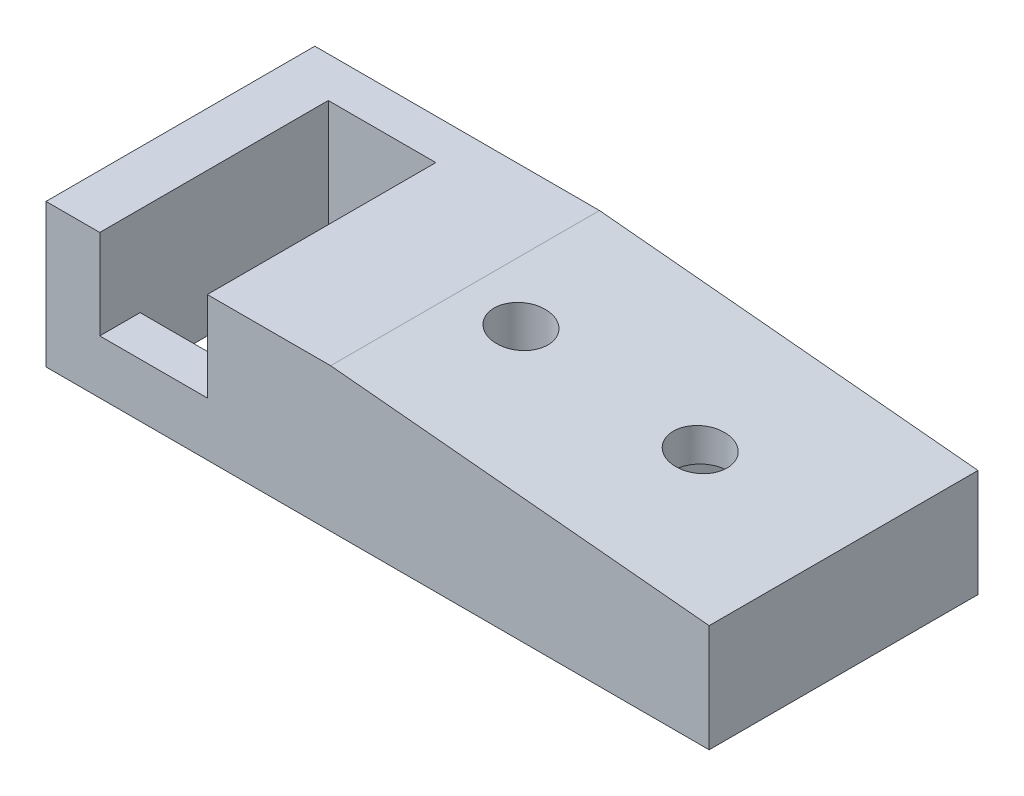
SolidWorks part; units mm, degrees
ref_plane "Front" through (0, 0, 0) normal (0, 0, 1) x (1, 0, 0)
ref_plane "Top" through (0, 0, 0) normal (0, 1, 0) x (1, 0, 0)
ref_plane "Right" through (0, 0, 0) normal (1, 0, 0) x (0, 0, -1)
sketch "Sketch1" plane through (0, 0, 0) normal (0, 0, 1) x (1, 0, 0)
  line L3 (0, 8.1782) -> (0, 0)
  line L4 (0, 0) -> (23, 0)
  line L5 (23, 0) -> (23, 6)
  line L6 (23, 6) -> (0, 8.1782)
  dimension "D1" = 23
  dimension "D2" = 6
  dimension "D3" = 5.41
extrude "Boss-Extrude1" add sketch "Sketch1" along normal blind 5
sketch "Sketch2" plane through (0, 0, 0) normal (0, -1, 0) x (-1, 0, 0)
  line L0 (-23, -2.5) -> (0, -2.5) construction
  line L1 (-23, -5) -> (-23, 0) construction
  line L2 (0, -5) -> (0, 0) construction
  circle A0 centre (-15, -2.5) radius 1.5
  circle A1 centre (-5, -2.5) radius 1.5
  dimension "D1" = 3
  dimension "D2" = 5
  dimension "D3" = 8
extrude "Cut-Extrude1" cut sketch "Sketch2" against normal blind 10
sketch "Sketch4" plane through (0, 0, 0) normal (0, -1, 0) x (-1, 0, 0)
  line L0 (0, -5) -> (-23, -5)
  line L1 (-23, -5) -> (-23, -10)
  line L2 (-23, -10) -> (14, -10)
  line L3 (0, -2.5) -> (14, -2.5) construction
  line L5 (14, 5) -> (14, -10)
  line L6 (0, -5) -> (0, 0)
  line L7 (-23, 5) -> (14, 5)
  line L8 (-23, 0) -> (-23, 5)
  line L9 (0, -5) -> (0, 0) construction
  line L10 (0, 0) -> (-23, 0)
  line L11 (11, 2.75) -> (11, -7.75)
  line L12 (11, -7.75) -> (5, -7.75)
  line L13 (5, -7.75) -> (5, 2.75)
  line L14 (11, 2.75) -> (5, 2.75)
  point P19 (11, -2.5)
  point P20 (5, -2.5)
  dimension "D1" = 5
  dimension "D2" = 37
  dimension "D3" = 6
  dimension "D4" = 5.25
  dimension "D5" = 5
extrude "Boss-Extrude2" add sketch "Sketch4" against normal blind 8
sketch "Sketch3" plane through (0, 0, 5) normal (0, 0, 1) x (1, 0, 0)
  line L0 (5, 0) -> (5, 7.7047) construction
  line L1 (0, 0) -> (23, 0) construction
  line L2 (1.8816, 8) -> (0, 8.1782) construction
  line L4 (15, 0) -> (15, 6.7576) construction
  line L5 (23, 0) -> (23, 6) construction
  line L6 (0, 8.1782) -> (0, 8) construction
  line L11 (2.25, 2) -> (7.75, 2)
  line L12 (2.25, 2) -> (2.25, 5)
  line L13 (2.25, 5) -> (7.75, 5)
  line L14 (7.75, 2) -> (7.75, 5)
  line L15 (2.25, 2) -> (7.75, 5) construction
  line L16 (2.25, 5) -> (7.75, 2) construction
  line L17 (12.25, 5) -> (17.75, 5)
  line L18 (12.25, 5) -> (12.25, 2)
  line L19 (12.25, 2) -> (17.75, 2)
  line L20 (17.75, 5) -> (17.75, 2)
  line L21 (12.25, 5) -> (17.75, 2) construction
  line L22 (12.25, 2) -> (17.75, 5) construction
  point P12 (5, 3.8523)
  point P13 (5, 3.5)
  point P18 (15, 3.5)
  dimension "D1" = 8
  dimension "D2" = 5
  dimension "D3" = 3
  dimension "D4" = 5.5
  dimension "D5" = 3
  dimension "D6" = 5.5
  dimension "D7" = 2
  dimension "D8" = 2
extrude "Cut-Extrude2" cut sketch "Sketch3" against normal through all
sketch "Sketch5" plane through (0, 0, 5) normal (0, 0, 1) x (1, 0, 0)
  line L0 (0, 8.1782) -> (23, 6)
  line L1 (23, 6) -> (23, 8)
  line L2 (23, 8) -> (0, 8)
  line L3 (23, 8) -> (-14, 8) construction
  line L4 (0, 8) -> (0, 8.1782)
  line L5 (1.8816, 8) -> (0, 8)
  line L6 (1.8816, 8) -> (23, 6)
  line L7 (23, 8) -> (1.8816, 8)
extrude "Cut-Extrude4" cut sketch "Sketch5" against normal through all both and the other way through all contours L1 L2 L0
sketch "Sketch9" plane through (0, 8, 0) normal (0, 1, 0) x (1, 0, 0)
  line L0 (-11, -7.75) -> (-11, -10)
  line L1 (1.8816, -10) -> (-14, -10) construction
  line L3 (-5, -7.75) -> (-5, -10)
  line L4 (-5, -10) -> (-11, -10)
  line L5 (-11, -7.75) -> (-5, -7.75)
extrude "Cut-Extrude5" cut sketch "Sketch9" against normal blind 5
